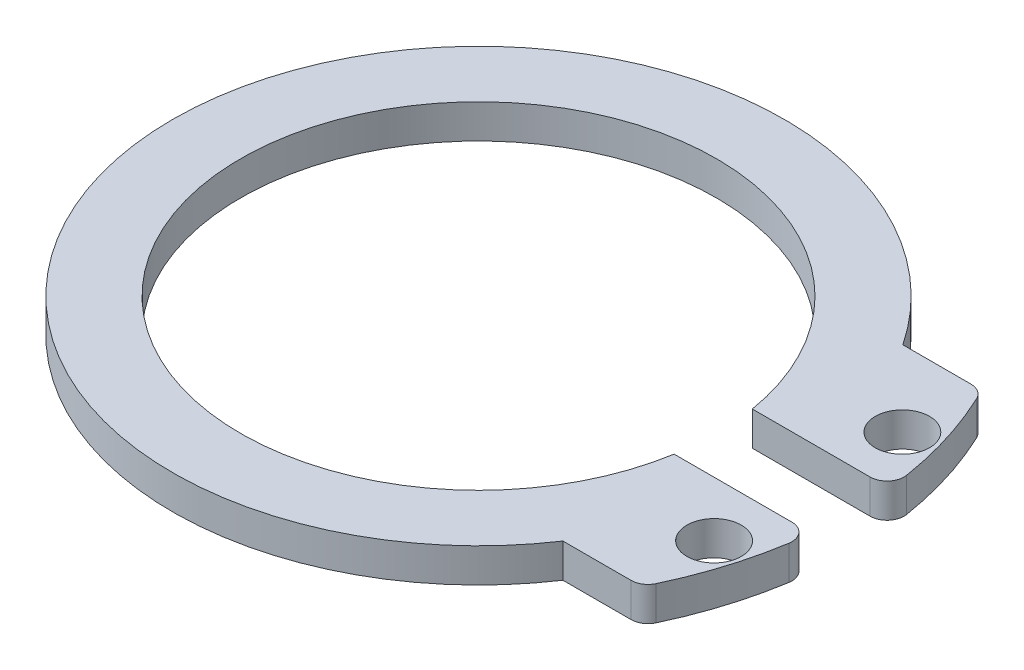
SolidWorks part; units mm, degrees
ref_plane "前视基准面" through (0, 0, 0) normal (0, 0, 1) x (1, 0, 0)
ref_plane "上视基准面" through (0, 0, 0) normal (0, 1, 0) x (1, 0, 0)
ref_plane "右视基准面" through (0, 0, 0) normal (1, 0, 0) x (0, 0, -1)
sketch "草图1" plane through (0, 0, 0) normal (0, 1, 0) x (1, 0, 0)
  circle A0 centre (0, 0) radius 8 construction
  circle A1 centre (0, 0) radius 9
  circle A2 centre (0, 0) radius 7
  dimension "D1" = 16
  dimension "D2" = 1
  dimension "D3" = 1
extrude "凸台-拉伸1" add sketch "草图1" along normal blind 1
sketch "草图2" plane through (0, 1, 0) normal (0, 1, 0) x (1, 0, 0)
  line L0 (0, 0) -> (1.5, 0) construction
  line L1 (10.9397, 1.15) -> (8.9262, 1.15)
  line L2 (10.9397, -1.15) -> (8.9262, -1.15)
  line L3 (9.798, 5) -> (7.4833, 5)
  line L4 (9.798, -5) -> (7.4833, -5)
  line L5 (9.7, 7.126) -> (9.7, -6.7692) construction
  arc A0 (10.9397, 1.15) -> (9.798, 5) centre (0, 0) ccw
  circle A1 centre (0, 0) radius 9 construction
  arc A2 (9.798, -5) -> (10.9397, -1.15) centre (0, 0) ccw
  arc A3 (7.4833, -5) -> (8.9262, -1.15) centre (0, 0) ccw
  arc A4 (8.9262, 1.15) -> (7.4833, 5) centre (0, 0) ccw
  circle A5 centre (9.7, 2.7695) radius 0.8
  circle A6 centre (9.7, -2.7695) radius 0.8
  point P12 (0.75, 0)
  point P20 (0, 0)
  dimension "D1" = 22
  dimension "D3" = 1.6
  dimension "D6" = 1.6
  dimension "D2" = 9.7
  dimension "D4" = 5
  dimension "D5" = 5
  dimension "D7" = 2.7695
extrude "凸台-拉伸2" add sketch "草图2" against normal up to surface (1 mm away) up to face at (0, 0, 9)
sketch "草图3" plane through (0, 1, 0) normal (0, 1, 0) x (1, 0, 0)
  line L0 (10.9397, 1.15) -> (4.4291, 1.15)
  line L1 (4.4291, 1.15) -> (4.4291, -1.15)
  line L2 (4.4291, -1.15) -> (10.9397, -1.15)
  line L3 (10.9397, -1.15) -> (10.9397, 1.15)
extrude "切除-拉伸1" cut sketch "草图3" against normal through all
fillet "圆角1" radius 0.5 4 edges at (9.798, 0.5, 5) (10.9397, 0.5, 1.15) (9.798, 0.5, -5) (10.9397, 0.5, -1.15)
